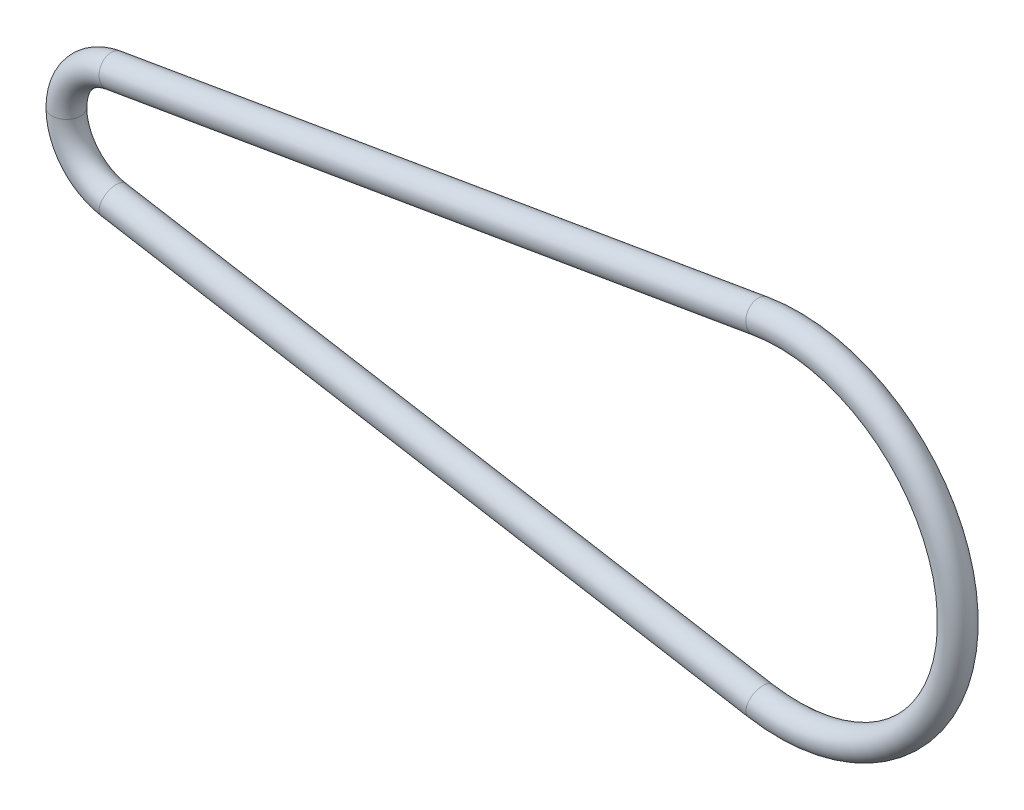
SolidWorks part; units mm, degrees
ref_plane "Front Plane" through (0, 0, 0) normal (0, 0, 1) x (1, 0, 0)
ref_plane "Top Plane" through (0, 0, 0) normal (0, 1, 0) x (1, 0, 0)
ref_plane "Right Plane" through (0, 0, 0) normal (1, 0, 0) x (0, 0, -1)
sketch "Sketch1" plane through (0, 0, 0) normal (0, 0, 1) x (1, 0, 0)
  line L0 (-0.8681, 5.0826) -> (57.7679, 15.0976)
  line L1 (-0.8681, -5.0826) -> (57.7679, -15.0976)
  arc A0 (-0.8681, -5.0826) -> (-0.8681, 5.0826) centre (0, 0) cw
  arc A1 (57.7679, 15.0976) -> (57.7679, -15.0976) centre (60.3466, 0) cw
  point P7 (0, 0)
  dimension "D1" = 5.1562
  dimension "D2" = 15.3162
  dimension "D3" = 186.7237
sketch "Sketch2" plane through (0, 0, 0) normal (0, 1, 0) x (1, 0, 0)
  line L0 (-5.1562, 0) -> (-0.8681, 0) construction
  line L1 (-5.1562, 0) -> (-0.8681, 0) construction
  circle A0 centre (-5.1562, 0) radius 1.3081
  dimension "D1" = 2.6162
sweep "Sweep1" add profiles "Sketch2" path "Sketch1"
